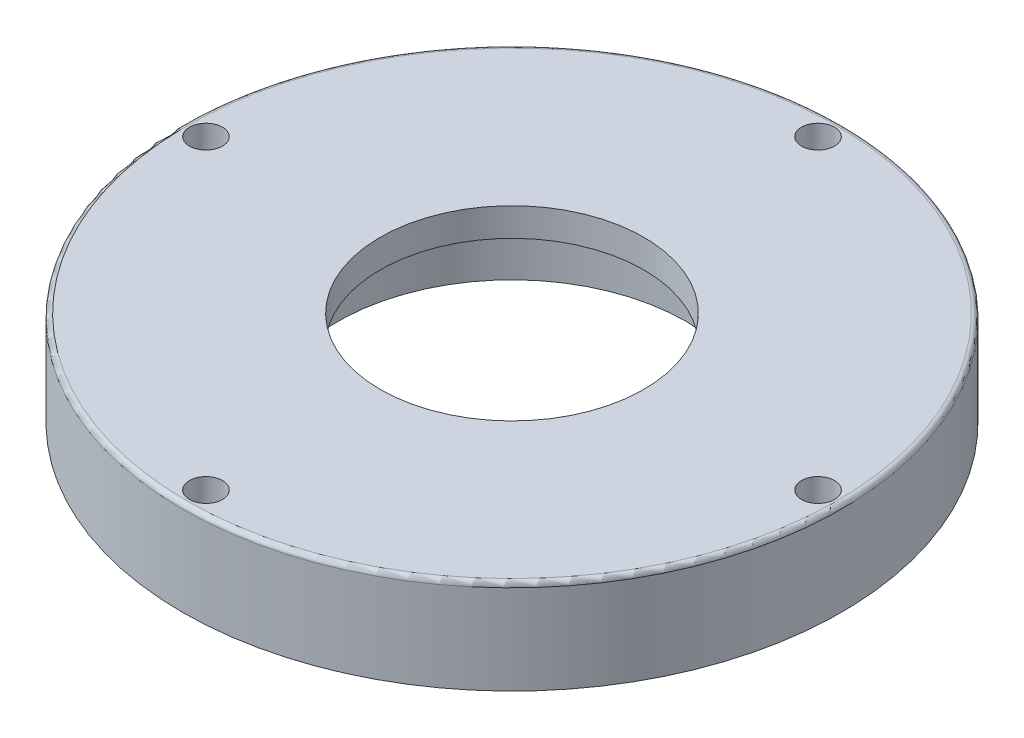
SolidWorks part; units mm, degrees
ref_plane "Front Plane" through (0, 0, 0) normal (0, 0, 1) x (1, 0, 0)
ref_plane "Top Plane" through (0, 0, 0) normal (0, 1, 0) x (1, 0, 0)
ref_plane "Right Plane" through (0, 0, 0) normal (1, 0, 0) x (0, 0, -1)
sketch "Sketch1" plane through (0, 0, 0) normal (0, 1, 0) x (1, 0, 0)
  line L0 (0, 0) -> (-68097.4901, 0) construction
  line L1 (0, 0) -> (0, -68097.4901) construction
  circle A0 centre (0, 0) radius 35
  dimension "D1" = 70
extrude "Boss-Extrude1" add sketch "Sketch1" along normal blind 10
sketch "Sketch2" plane through (0, 10, 0) normal (0, 1, 0) x (1, 0, 0)
  line L0 (0, 0) -> (-50000, 0) construction
  line L1 (0, 0) -> (0, -50000) construction
  circle A0 centre (0, 0) radius 32.5 construction
  circle A1 centre (0, 32.5) radius 1.75
  circle A2 centre (32.5, 0) radius 1.75
  circle A3 centre (0, -32.5) radius 1.75
  circle A4 centre (-32.5, 0) radius 1.75
  point P18 (0, 0)
  dimension "D1" = 65
  dimension "D2" = 3.5
extrude "Cut-Extrude1" cut sketch "Sketch2" against normal through all
sketch "Sketch4" plane through (0, 0, 0) normal (0, -1, 0) x (1, 0, 0)
  line L0 (0, 0) -> (-50000, 0) construction
  line L1 (0, 0) -> (0, -50000) construction
  circle A0 centre (0, 0) radius 18.5
  dimension "D1" = 37
extrude "Cut-Extrude2" cut sketch "Sketch4" against normal blind 7
sketch "Sketch5" plane through (0, 10, 0) normal (0, 1, 0) x (1, 0, 0)
  line L0 (0, 0) -> (-50000, 0) construction
  line L1 (0, 0) -> (0, -50000) construction
  circle A0 centre (0, 0) radius 14
  dimension "D1" = 28
extrude "Cut-Extrude3" cut sketch "Sketch5" against normal through all
fillet "Fillet1" radius 0.5 1 edges at (0, 10, 35)
